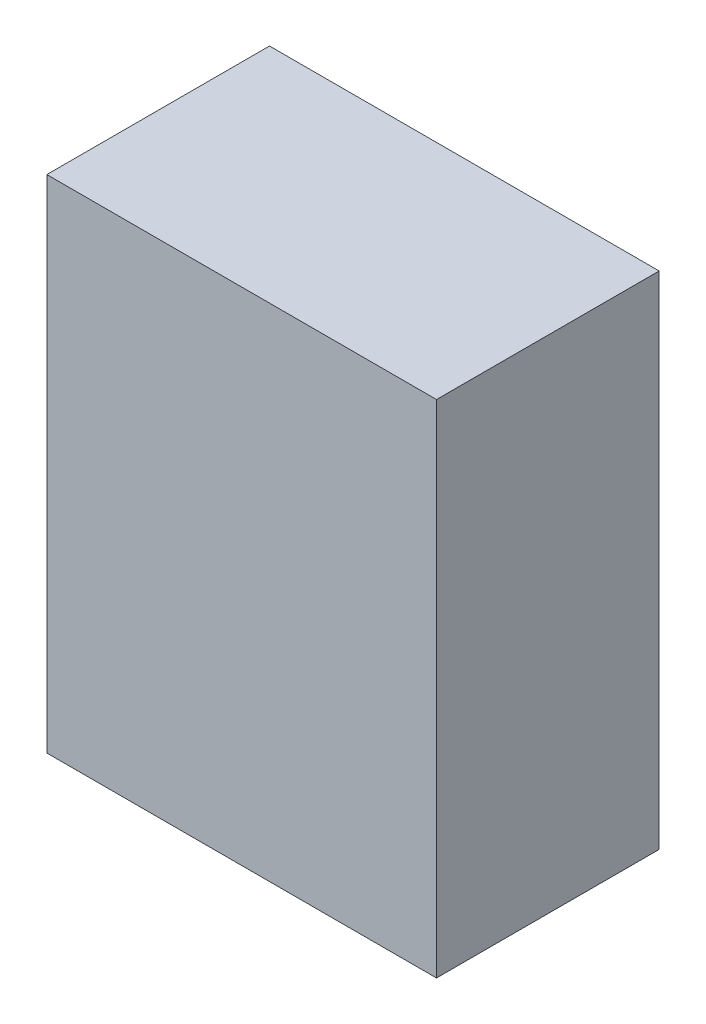
SolidWorks part; units mm, degrees
ref_plane "Front Plane" through (0, 0, 0) normal (0, 0, 1) x (1, 0, 0)
ref_plane "Top Plane" through (0, 0, 0) normal (0, 1, 0) x (1, 0, 0)
ref_plane "Right Plane" through (0, 0, 0) normal (1, 0, 0) x (0, 0, -1)
sketch "Sketch1" plane through (0, 0, 0) normal (0, 0, 1) x (1, 0, 0)
  line L1 (-35, 45) -> (35, 45)
  line L2 (-35, 45) -> (-35, -45)
  line L3 (-35, -45) -> (35, -45)
  line L4 (35, 45) -> (35, -45)
  line L5 (-35, 45) -> (35, -45) construction
  line L6 (-35, -45) -> (35, 45) construction
  point P0 (0, 0)
extrude "Boss-Extrude1" add sketch "Sketch1" along normal blind 40
